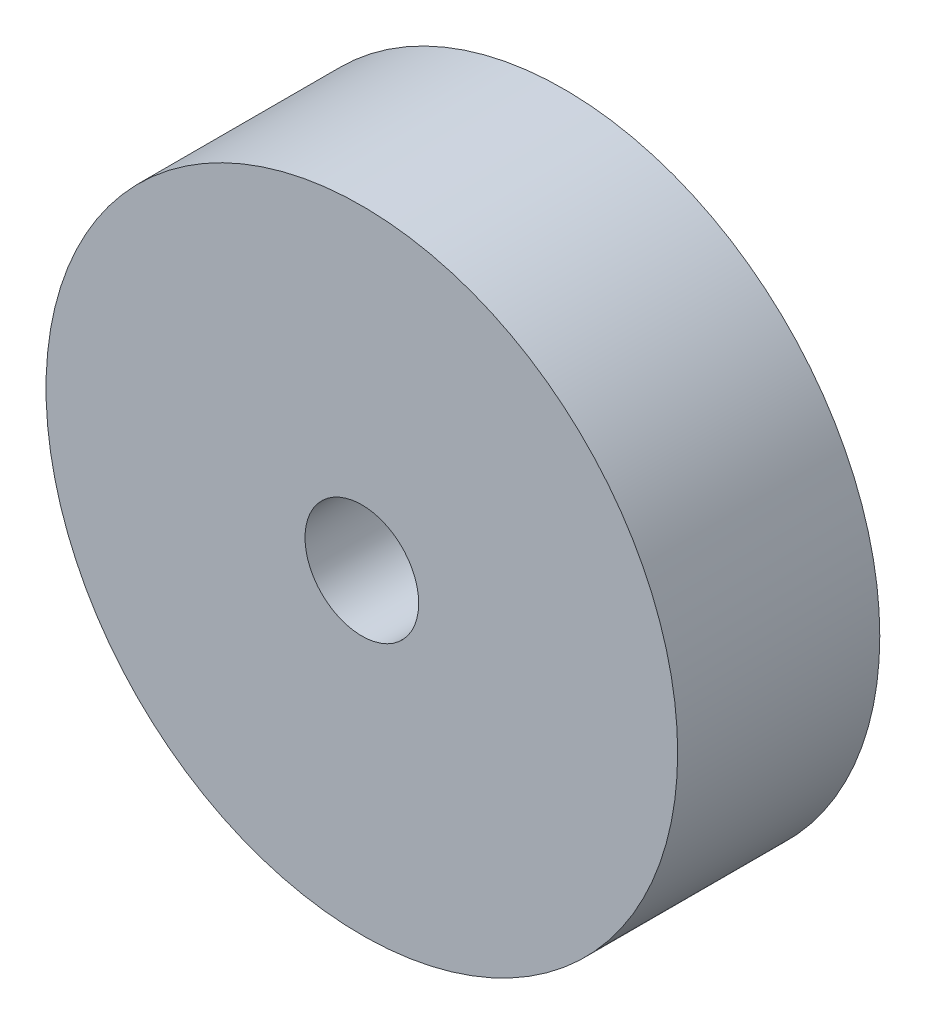
SolidWorks part; units mm, degrees
material "POLYURETHANE (11671)"
ref_plane "Face" through (0, 0, 0) normal (0, 0, 1) x (1, 0, 0)
ref_plane "Dessus" through (0, 0, 0) normal (0, 1, 0) x (1, 0, 0)
ref_plane "Droite" through (0, 0, 0) normal (1, 0, 0) x (0, 0, -1)
sketch "Esquisse1" plane through (0, 0, 0) normal (0, 0, 1) x (1, 0, 0)
  circle A0 centre (0, 0) radius 2.25
  circle A1 centre (0, 0) radius 12.5
  dimension "D1" = 25
  dimension "D2" = 4.5
extrude "Boss.-Extru.1" add sketch "Esquisse1" along normal blind 8
